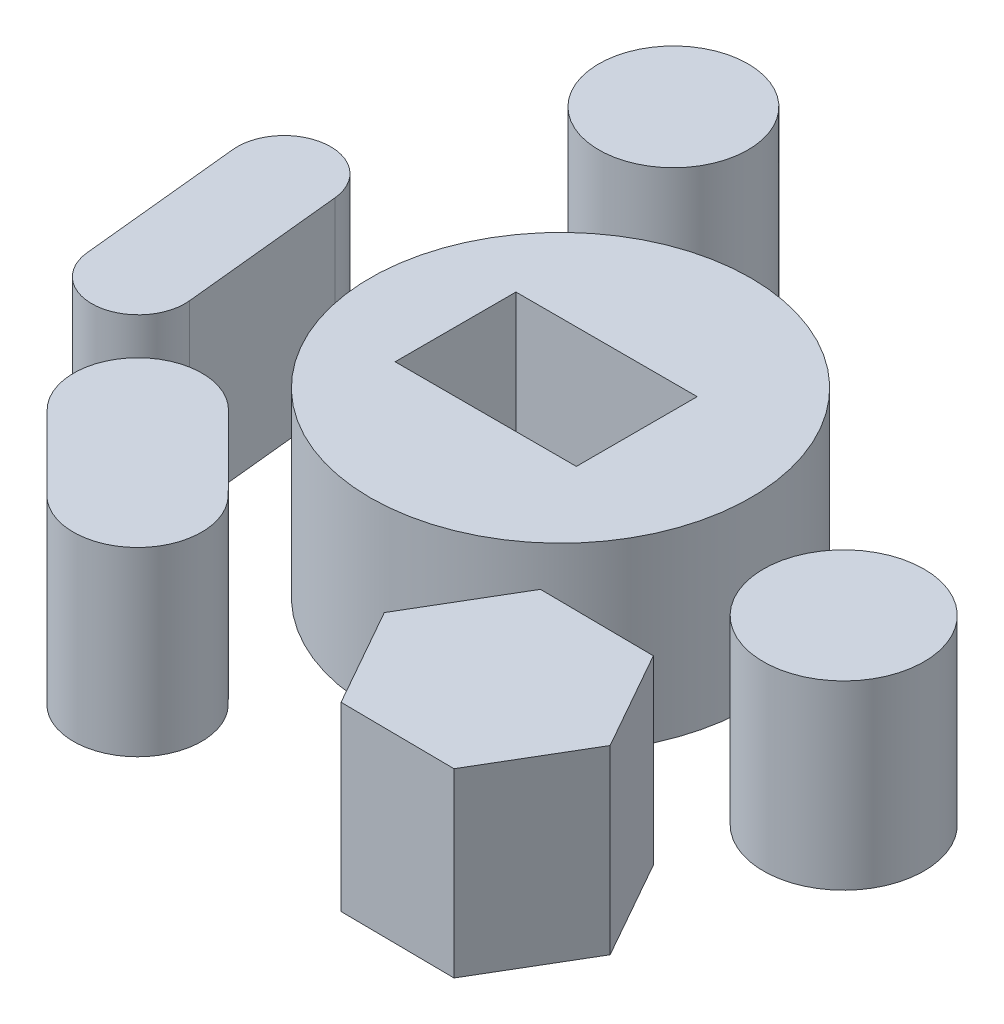
SolidWorks part; units mm, degrees
ref_plane "Front Plane" through (0, 0, 0) normal (0, 0, 1) x (1, 0, 0)
ref_plane "Top Plane" through (0, 0, 0) normal (0, 1, 0) x (1, 0, 0)
ref_plane "Right Plane" through (0, 0, 0) normal (1, 0, 0) x (0, 0, -1)
sketch "Sketch1" plane through (0, 0, 0) normal (0, 1, 0) x (1, 0, 0)
  line L0 (-183.7469, 90.3135) -> (-169.9051, -46.0269) construction
  line L1 (0, 0) -> (152.4, 0)
  line L2 (0, 0) -> (0, 101.6)
  line L3 (0, 101.6) -> (152.4, 101.6)
  line L4 (152.4, 0) -> (152.4, 101.6)
  line L5 (225.2265, -270.6605) -> (321.0882, -271.5805)
  line L6 (321.0882, -271.5805) -> (369.8158, -189.0218)
  line L7 (369.8158, -189.0218) -> (322.6817, -105.5431)
  line L8 (322.6817, -105.5431) -> (226.82, -104.6231)
  line L9 (226.82, -104.6231) -> (178.0924, -187.1818)
  line L10 (178.0924, -187.1818) -> (225.2265, -270.6605)
  line L11 (-144.7158, 94.2761) -> (-130.8739, -42.0642)
  line L12 (-222.778, 86.3509) -> (-208.9362, -49.9895)
  line L13 (-11.1846, -205.4234) -> (-72.9666, -143.3782) construction
  line L14 (-49.4047, -243.4814) -> (-111.1867, -181.4362)
  line L15 (27.0355, -167.3655) -> (-34.7466, -105.3203)
  circle A0 centre (88.5054, 50.5784) radius 160.0544
  circle A1 centre (373.2899, 3.911) radius 67.5466
  circle A2 centre (273.9541, -188.1018) radius 83.0225 construction
  circle A3 centre (-68.6385, 302.6432) radius 62.7284
  arc A4 (-144.7158, 94.2761) -> (-222.778, 86.3509) centre (-183.7469, 90.3135) ccw
  arc A5 (-208.9362, -49.9895) -> (-130.8739, -42.0642) centre (-169.9051, -46.0269) ccw
  arc A6 (-49.4047, -243.4814) -> (27.0355, -167.3655) centre (-11.1846, -205.4234) ccw
  arc A7 (-34.7466, -105.3203) -> (-111.1867, -181.4362) centre (-72.9666, -143.3782) ccw
  point P21 (-176.826, 22.1433)
  point P26 (-42.0756, -174.4008)
  dimension "D1" = 152.4
  dimension "D2" = 101.6
extrude "Boss-Extrude1" add sketch "Sketch1" along normal blind 152.4
sketch "Sketch2" plane through (-146.5469, 0, 145.9253) normal (-0.7086, 0, 0.7056) x (0.7056, 0, 0.7086)
  circle A0 centre (89.9102, 73.7698) radius 27.2038
extrude "Cut-Extrude1" cut sketch "Sketch2" against normal mid plane 76.2
